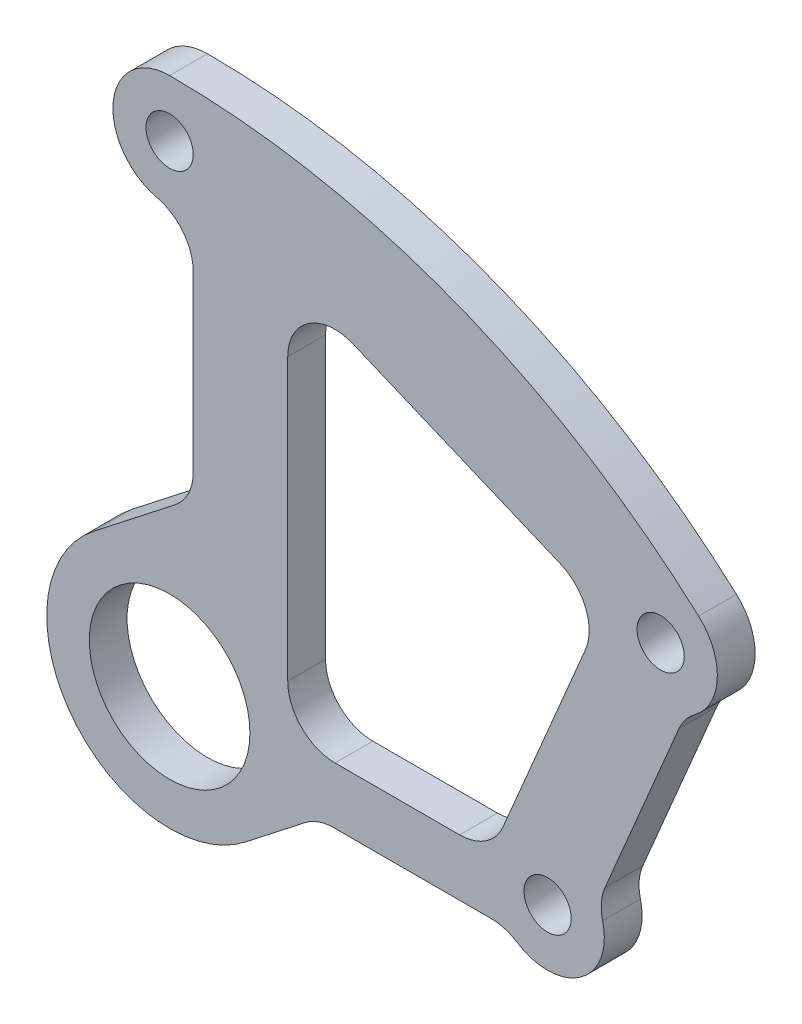
SolidWorks part; units mm, degrees
other "Weld Folder"
ref_plane "Płaszczyzna przednia" through (0, 0, 0) normal (0, 0, 1) x (1, 0, 0)
ref_plane "Płaszczyzna górna" through (0, 0, 0) normal (0, 1, 0) x (1, 0, 0)
ref_plane "Płaszczyzna prawa" through (0, 0, 0) normal (1, 0, 0) x (0, 0, -1)
sketch "Sketch1" plane through (0, 0, 0) normal (0, 0, 1) x (1, 0, 0)
  line L0 (103.923, 60) -> (0, 0) construction
  line L1 (0, 0) -> (80, 0) construction
  line L3 (5, 78.5757) -> (5, 41.7782)
  line L4 (-16.0072, 20.4883) -> (16.0072, -20.4883) construction
  line L5 (1.1566, 33.8981) -> (-16.0072, 20.4883)
  line L6 (25, 72.9761) -> (25, 13.5147)
  line L7 (35, 3.5147) -> (61.3754, 3.5147)
  line L8 (70.5836, 9.6148) -> (88.0061, 50.7516)
  line L9 (82.6576, 63.8766) -> (38.8597, 82.2012)
  line L10 (80, 0) -> (76.4645, 3.5355) construction
  line L11 (80, 0) -> (71.5147, -8.4853) construction
  line L12 (107.8062, 46.2189) -> (92.1379, 9.224)
  line L13 (68.0713, -8.4853) -> (34.8136, -8.4853)
  line L14 (16.0072, -20.4883) -> (28.657, -10.6052)
  line L15 (5, 88) -> (5, 100) construction
  line L17 (5, 78.5757) -> (5, 88) construction
  circle A0 centre (0, 0) radius 17
  circle A1 centre (0, 100) radius 5
  circle A2 centre (80, 0) radius 5
  circle A3 centre (103.923, 60) radius 5
  arc A4 (0, 112) -> (-2.7273, 88.314) centre (0, 100) ccw
  arc A5 (-16.0072, 20.4883) -> (16.0072, -20.4883) centre (0, 0) ccw
  arc A6 (91.6433, 2.9041) -> (73.4934, -10.0829) centre (80, 0) cw
  arc A7 (111.0638, 50.3558) -> (111.9687, 68.9032) centre (103.923, 60) ccw
  arc A8 (0, 112) -> (111.9687, 68.9032) centre (0, -55) cw
  arc A9 (5, 78.5757) -> (-2.7273, 88.314) centre (-5, 78.5757) ccw
  arc A10 (34.8136, -8.4853) -> (28.657, -10.6052) centre (34.8136, -18.4853) ccw
  arc A11 (73.4934, -10.0829) -> (68.0713, -8.4853) centre (68.0713, -18.4853) ccw
  arc A12 (91.6433, 2.9041) -> (92.1379, 9.224) centre (101.346, 5.3241) cw
  arc A13 (111.0638, 50.3558) -> (107.8062, 46.2189) centre (117.0144, 42.319) ccw
  arc A14 (25, 72.9761) -> (38.8597, 82.2012) centre (35, 72.9761) cw
  arc A15 (88.0061, 50.7516) -> (82.6576, 63.8766) centre (78.7979, 54.6515) ccw
  arc A16 (61.3754, 3.5147) -> (70.5836, 9.6148) centre (61.3754, 13.5147) ccw
  arc A17 (35, 3.5147) -> (25, 13.5147) centre (35, 13.5147) cw
  arc A18 (1.1566, 33.8981) -> (5, 41.7782) centre (-5, 41.7782) ccw
  point P27 (98.9151, 67.9397)
  point P42 (25, 88)
  point P45 (91.923, 60)
  point P48 (68, 3.5147)
  dimension "D1" = 10
  dimension "D2" = 10
  dimension "D3" = 10
  dimension "D4" = 120
  dimension "34" = 34
  dimension "D10" = 9
  dimension "D11" = 7
  dimension "D12" = 7
  dimension "D13" = 7
  dimension "D21" = 10
  dimension "D23" = 10
  dimension "D5" = 128
  dimension "D6" = 100
  dimension "D7" = 30
  dimension "D8" = 80
  dimension "D14" = 90
  dimension "D15" = 45
  dimension "D16" = 12
  dimension "D17" = 20
  dimension "D18" = 20
  dimension "D19" = 12
  dimension "D20" = 12
  dimension "D22" = 12
extrude "Boss-Extrude1" add sketch "Sketch1" along normal mid plane 8
equation "\"d\"= 10'dziura pod pushrody"
equation "\"g\"= 7'grubość dookoła otworów"
equation "\"D4\"=28"
